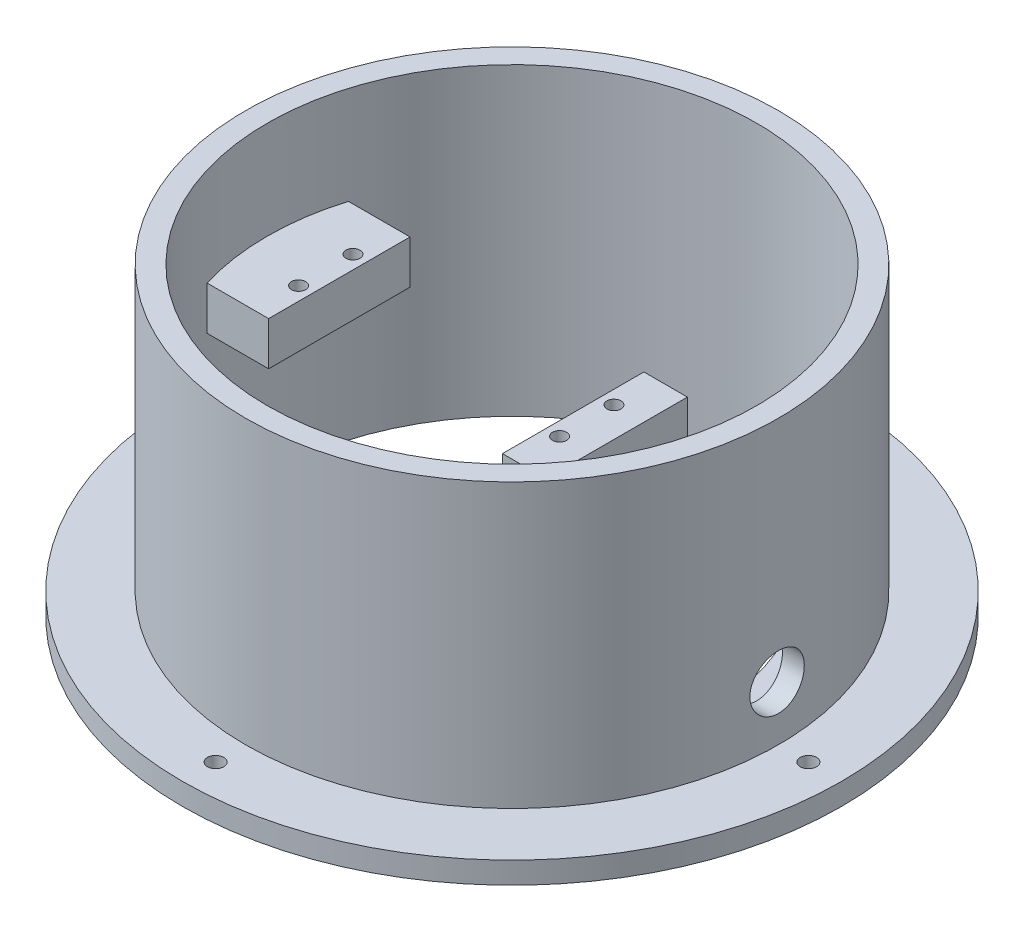
SolidWorks part; units mm, degrees
ref_plane "Front Plane" through (0, 0, 0) normal (0, 0, 1) x (1, 0, 0)
ref_plane "Top Plane" through (0, 0, 0) normal (0, 1, 0) x (1, 0, 0)
ref_plane "Right Plane" through (0, 0, 0) normal (1, 0, 0) x (0, 0, -1)
sketch "Sketch1" plane through (0, 0, 0) normal (0, 1, 0) x (1, 0, 0)
  circle A0 centre (0, 0) radius 45
  circle A1 centre (0, 0) radius 60.625
  dimension "D1" = 90
  dimension "D2" = 121.25
extrude "Boss-Extrude1" add sketch "Sketch1" along normal blind 4
sketch "Sketch2" plane through (0, 4, 0) normal (0, 1, 0) x (1, 0, 0)
  circle A0 centre (0, 0) radius 49
  circle A1 centre (0, 0) radius 45
  dimension "D1" = 98
extrude "Boss-Extrude2" add sketch "Sketch2" along normal blind 52
sketch "Sketch3" plane through (0, 0, 0) normal (0, 0, 1) x (1, 0, 0)
  line L0 (-60.625, 0) -> (60.625, 0) construction
  line L1 (11.25, 0) -> (19.25, 0)
  line L2 (11.25, 0) -> (11.25, 38)
  line L3 (11.25, 38) -> (19.25, 38)
  line L4 (19.25, 0) -> (19.25, 38)
  line L5 (45, 56) -> (-45, 56) construction
  line L6 (-46.75, 38) -> (-31.75, 38)
  line L7 (-46.75, 38) -> (-46.75, 30)
  line L8 (-46.75, 30) -> (-31.75, 30)
  line L9 (-31.75, 38) -> (-31.75, 30)
  dimension "D1" = 8
  dimension "D2" = 38
  dimension "D3" = 11.25
  dimension "D4" = 8
  dimension "D5" = 15
  dimension "D6" = 43
  dimension "D7" = 18
extrude "Boss-Extrude3" add sketch "Sketch3" along normal mid plane 26
sketch "Sketch4" plane through (0, 38, 0) normal (0, 1, 0) x (1, 0, 0)
  line L0 (-31.75, -13) -> (-31.75, 13) construction
  line L1 (11.25, -13) -> (11.25, 13) construction
  circle A0 centre (13.75, 5) radius 1.3
  circle A1 centre (13.75, -5) radius 1.3
  circle A2 centre (-34.25, 5) radius 1.3
  circle A3 centre (-34.25, -5) radius 1.3
  dimension "D9" = 2.6
  dimension "D1" = 2.5
  dimension "D2" = 2.5
  dimension "D3" = 5
  dimension "D4" = 5
  dimension "D5" = 5
  dimension "D6" = 5
  dimension "D7" = 2.5
  dimension "D8" = 2.5
extrude "Cut-Extrude1" cut sketch "Sketch4" against normal blind 7.2
sketch "Sketch5" plane through (0, 0, 0) normal (0, -1, 0) x (1, 0, 0)
  line L0 (11.25, 13) -> (25.2498, 37.2484)
  line L1 (0, 0) -> (85.5494, 0) construction
  line L2 (11.25, -13) -> (25.2498, -37.2484)
  line L3 (11.25, 13) -> (11.25, -13)
  line L5 (24.25, -19.5167) -> (27.3618, -24.9065)
  line L6 (24.25, 19.5167) -> (27.3618, 24.9065)
  line L7 (24.25, 19.5167) -> (24.25, -19.5167)
  line L8 (19.25, 13) -> (19.25, -13) construction
  line L10 (19.25, 10.8564) -> (27.3618, 24.9065) construction
  line L11 (19.25, 10.8564) -> (19.25, -10.8564) construction
  line L12 (19.25, -10.8564) -> (27.3618, -24.9065) construction
  circle A0 centre (0, 0) radius 45 construction
  arc A1 (25.2498, -37.2484) -> (25.2498, 37.2484) centre (0, 0) ccw
  arc A2 (27.3618, -24.9065) -> (27.3618, 24.9065) centre (0, 0) ccw
  dimension "D1" = 8
  dimension "60" = 60
  dimension "D2" = 5
extrude "Boss-Extrude4" add sketch "Sketch5" against normal blind 4
sketch "Sketch7" plane through (11.25, 0, 0) normal (-1, 0, 0) x (0, 0, 1)
  line L0 (-60.625, 0) -> (60.625, 0) construction
  line L1 (5, 5) -> (-5, 5)
  line L2 (5, 5) -> (5, 29)
  line L3 (5, 29) -> (-5, 29)
  line L4 (-5, 5) -> (-5, 29)
  line L5 (5, 5) -> (-5, 29) construction
  line L6 (5, 29) -> (-5, 5) construction
  line L7 (0, 0) -> (0, 43.7162) construction
  point P0 (0, 17)
  dimension "D1" = 5
  dimension "D2" = 24
  dimension "D3" = 10
extrude "Cut-Extrude2" cut sketch "Sketch7" against normal up to surface (8 mm away) up to face at (19.25, 21, 0)
sketch "Sketch8" plane through (11.25, 0, 0) normal (-1, 0, 0) x (0, 0, 1)
  line L0 (0, 0) -> (0, 62.5956) construction
  line L1 (-60.625, 0) -> (60.625, 0) construction
  circle A0 centre (0, 14) radius 5
  dimension "D1" = 14
  dimension "D2" = 10
extrude "Cut-Extrude3" cut sketch "Sketch8" against normal through all
sketch "Sketch9" plane through (0, 0, 0) normal (0, -1, 0) x (1, 0, 0)
  circle A0 centre (0, 0) radius 54.5 construction
  circle A1 centre (54.5, 0) radius 1.5
  circle A2 centre (0, -54.5) radius 1.5
  circle A3 centre (-54.5, 0) radius 1.5
  circle A4 centre (0, 54.5) radius 1.5
  point P14 (0, 0)
  dimension "D1" = 109
  dimension "D2" = 3
  dimension "D3" = 4
extrude "Cut-Extrude4" cut sketch "Sketch9" against normal up to next
